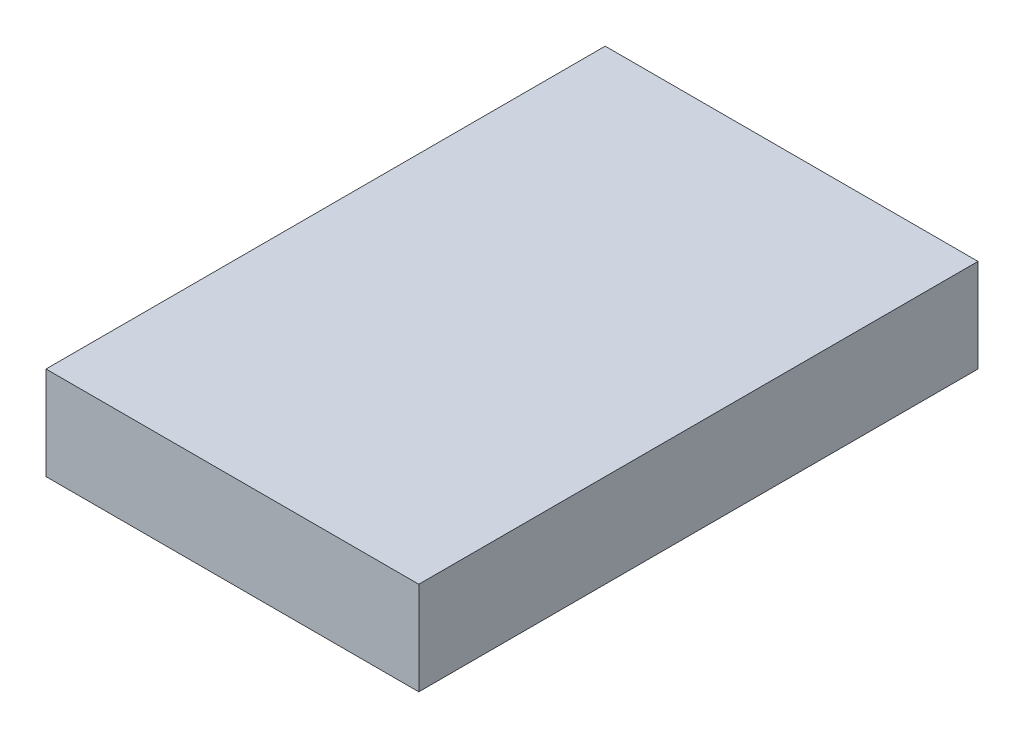
SolidWorks part; units mm, degrees
ref_plane "Front Plane" through (0, 0, 0) normal (0, 0, 1) x (1, 0, 0)
ref_plane "Top Plane" through (0, 0, 0) normal (0, 1, 0) x (1, 0, 0)
ref_plane "Right Plane" through (0, 0, 0) normal (1, 0, 0) x (0, 0, -1)
sketch "Sketch1" plane through (0, 0, 0) normal (0, 1, 0) x (1, 0, 0)
  line L1 (-10, -15) -> (10, -15)
  line L2 (-10, -15) -> (-10, 15)
  line L3 (-10, 15) -> (10, 15)
  line L4 (10, -15) -> (10, 15)
  line L5 (-10, -15) -> (10, 15) construction
  line L6 (-10, 15) -> (10, -15) construction
  point P0 (0, 0)
  dimension "D1" = 20
  dimension "D2" = 30
extrude "Boss-Extrude1" add sketch "Sketch1" along normal blind 5
